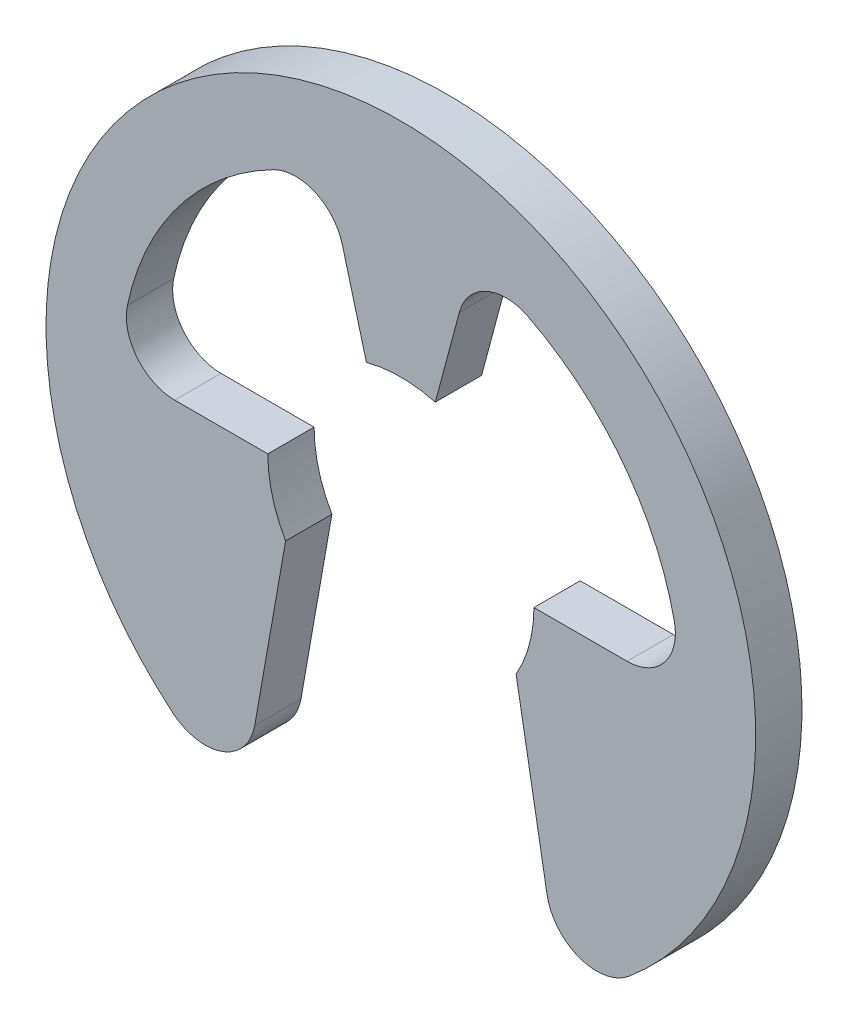
SolidWorks part; units mm, degrees
ref_plane "Plane1" through (0, 0, 0) normal (0, 0, 1) x (1, 0, 0)
ref_plane "Plane2" through (0, 0, 0) normal (0, 1, 0) x (1, 0, 0)
ref_plane "Plane3" through (0, 0, 0) normal (1, 0, 0) x (0, 0, -1)
sketch "Clipboard" plane through (0, 0, 0) normal (0, 0, 1) x (1, 0, 0)
  line L0 (0, 0) -> (0.65, 0)
  circle A0 centre (0, 0) radius 1.05
  circle A1 centre (0, 0) radius 2.8
  dimension "FreeID" = 2.1
  dimension "FreeOD" = 5.6
  dimension "Bridge" = 0.65
sketch "BodySke" plane through (0, 0, 0) normal (0, 0, 1) x (1, 0, 0)
  line L0 (-0.7581, 0) -> (0.7581, 0) construction
  line L1 (0, 0) -> (0, 1.15) construction
  line L2 (0, 0) -> (0.1962, 0.7323) construction
  line L3 (0, 0) -> (0.9959, -0.575) construction
  line L4 (0, 0) -> (-0.1962, 0.7323) construction
  line L5 (0, 0) -> (-0.9959, -0.575) construction
  line L6 (0.9959, -0.575) -> (1.2632, -2.0906)
  line L7 (-0.9959, -0.575) -> (-1.2632, -2.0906)
  line L9 (1.15, 0) -> (1.9545, 0)
  line L10 (-1.15, 0) -> (-1.9545, 0)
  line L11 (0.2976, 1.1108) -> (0.5059, 1.8879)
  line L12 (-0.2976, 1.1108) -> (-0.5059, 1.8879)
  circle A0 centre (0, 0) radius 1.15 construction
  arc A1 (2.3632, 0.5054) -> (1.0998, 2.1519) centre (0, 0) ccw
  arc A2 (1.9721, -2.3485) -> (-1.9721, -2.3485) centre (0, 0) ccw
  arc A3 (0.9959, -0.575) -> (1.15, 0) centre (0, 0) ccw
  arc A4 (-1.0998, 2.1519) -> (-2.3632, 0.5054) centre (0, 0) ccw
  arc A5 (-1.15, 0) -> (-0.9959, -0.575) centre (0, 0) ccw
  arc A6 (-0.2976, 1.1108) -> (0.2976, 1.1108) centre (0, 0) cw
  arc A7 (1.0998, 2.1519) -> (0.5059, 1.8879) centre (0.9096, 1.7797) ccw
  arc A8 (1.2632, -2.0906) -> (1.9721, -2.3485) centre (1.692, -2.0149) ccw
  arc A9 (-1.9721, -2.3485) -> (-1.2632, -2.0906) centre (-1.692, -2.0149) ccw
  arc A10 (-2.3632, 0.5054) -> (-1.9545, 0) centre (-1.9545, 0.418) ccw
  arc A11 (-0.5059, 1.8879) -> (-1.0998, 2.1519) centre (-0.9096, 1.7797) ccw
  arc A12 (1.9545, 0) -> (2.3632, 0.5054) centre (1.9545, 0.418) ccw
  dimension "GrooveDia" = 2.3
  dimension "OutsideDia" = 6.1333
  dimension "TipRad" = 0.4355
  dimension "CavityDia" = 4.8333
  dimension "CavityFilletRad" = 0.418
  dimension "D1" = 30
  dimension "D3" = 30
  dimension "D4" = 20
extrude "Body" add sketch "BodySke" against normal blind 0.4
equation "' \"FreeID@Clipboard\" = 0.64"
equation "' \"Thickness@Body\" = 0.25"
equation "' \"GrooveDia@BodySke\" = 0.72"
equation "' \"FreeOD@Clipboard\" = 2"
equation "' \"Bridge@Clipboard\" = 0.3"
equation "' \"FreeID@Clipboard\" = 19.5"
equation "' \"Thickness@Body\" = 1.3"
equation "' \"GrooveDia@BodySke\" = 20.00"
equation "' \"FreeOD@Clipboard\" = 37.1"
equation "' \"Bridge@Clipboard\" = 3.3"
equation "\"OutsideDia@BodySke\" = ( \"GrooveDia@BodySke\"  /  \"FreeID@Clipboard\" )  * \"FreeOD@Clipboard\""
equation "\"CavityDia@BodySke\" = \"OutsideDia@BodySke\"  - 2 * \"Bridge@Clipboard\""
equation "\"CavityFilletRad@BodySke\" =  (\"CavityDia@BodySke\" - \"GrooveDia@BodySke\") / 2 * 0.33"
equation "\"TipRad@BodySke\" = 0.67 * \"Bridge@Clipboard\""
